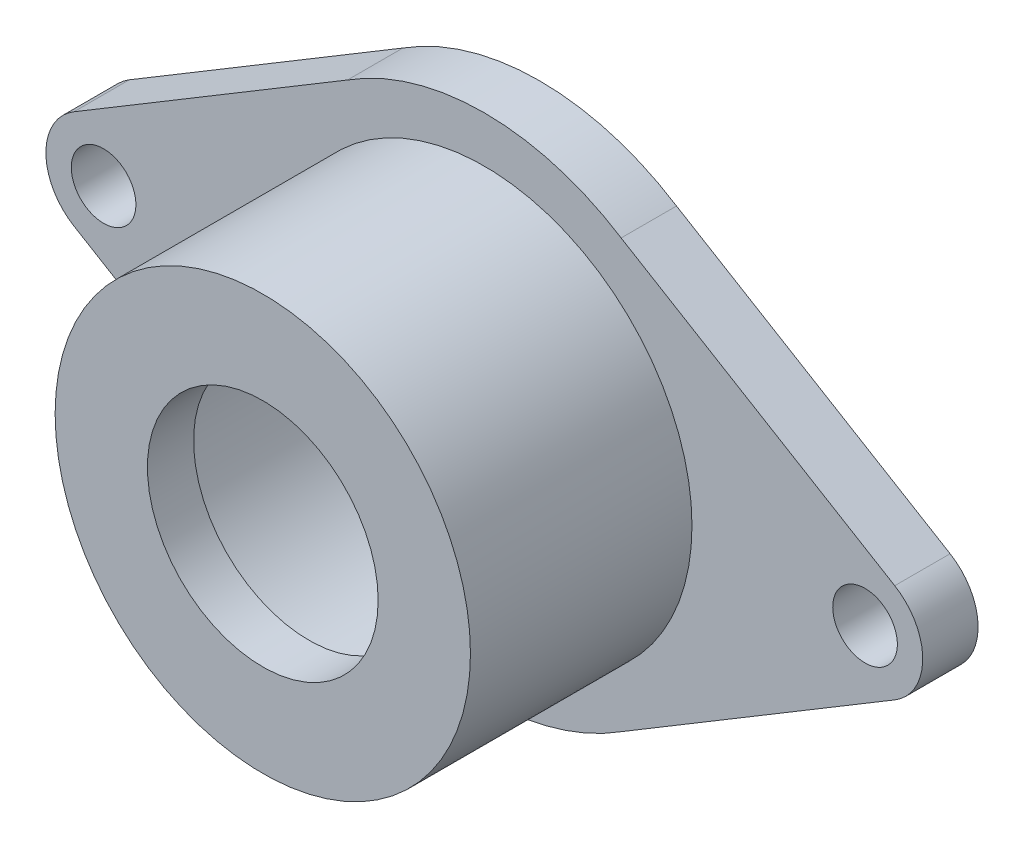
SolidWorks part; units mm, degrees
material "ASTM A36 Steel"
ref_plane "Front Plane" through (0, 0, 0) normal (0, 0, 1) x (1, 0, 0)
ref_plane "Top Plane" through (0, 0, 0) normal (0, 1, 0) x (1, 0, 0)
ref_plane "Right Plane" through (0, 0, 0) normal (1, 0, 0) x (0, 0, -1)
sketch "Sketch1" plane through (0, 0, 0) normal (1, 0, 0) x (0, 0, -1)
  line L0 (-59.4712, 1.4904) -> (-119.4712, 1.4904)
  line L1 (-119.4712, 1.4904) -> (-119.4712, -18.5096)
  line L2 (-119.4712, -18.5096) -> (-109.4712, -18.5096)
  line L3 (-109.4712, -18.5096) -> (-109.4712, -8.5096)
  line L4 (-109.4712, -8.5096) -> (-59.4712, -8.5096)
  line L5 (-59.4712, -8.5096) -> (-59.4712, 1.4904)
  line L6 (-119.4712, -43.5096) -> (44.4712, -43.5096)
  dimension "D1" = 25
  dimension "D2" = 10
  dimension "D3" = 10
  dimension "D4" = 10
  dimension "D5" = 60
revolve "Revolve2" add sketch "Sketch1" angle 360 about L6
sketch "Sketch3" plane through (0, 0, 59.4712) normal (0, 0, -1) x (-1, 0, 0)
  line L2 (-29.6477, -89.8347) -> (-88.936, -54.2254)
  line L3 (-29.6477, 2.8155) -> (-88.936, -32.7939)
  line L4 (29.6477, -89.8347) -> (88.936, -54.2254)
  line L5 (29.6477, 2.8155) -> (88.936, -32.7939)
  arc A0 (29.6477, 2.8155) -> (-29.6477, 2.8155) centre (0, -43.5096) ccw
  arc A1 (-29.6477, -89.8347) -> (29.6477, -89.8347) centre (0, -43.5096) ccw
  arc A2 (-88.936, -32.7939) -> (-88.936, -54.2254) centre (-82.5, -43.5096) ccw
  arc A3 (88.936, -32.7939) -> (88.936, -54.2254) centre (82.5, -43.5096) cw
  circle A4 centre (0, -43.5096) radius 45
  dimension "D1" = 110
  dimension "D4" = 25
extrude "Boss-Extrude1" add sketch "Sketch3" against normal blind 12
sketch "Sketch4" plane through (0, 0, 59.4712) normal (0, 0, -1) x (-1, 0, 0)
  circle A0 centre (-82.5, -43.5096) radius 7
  circle A1 centre (82.5, -43.5096) radius 7
  dimension "D1" = 14
  dimension "D2" = 14
extrude "Cut-Extrude1" cut sketch "Sketch4" against normal blind 12
